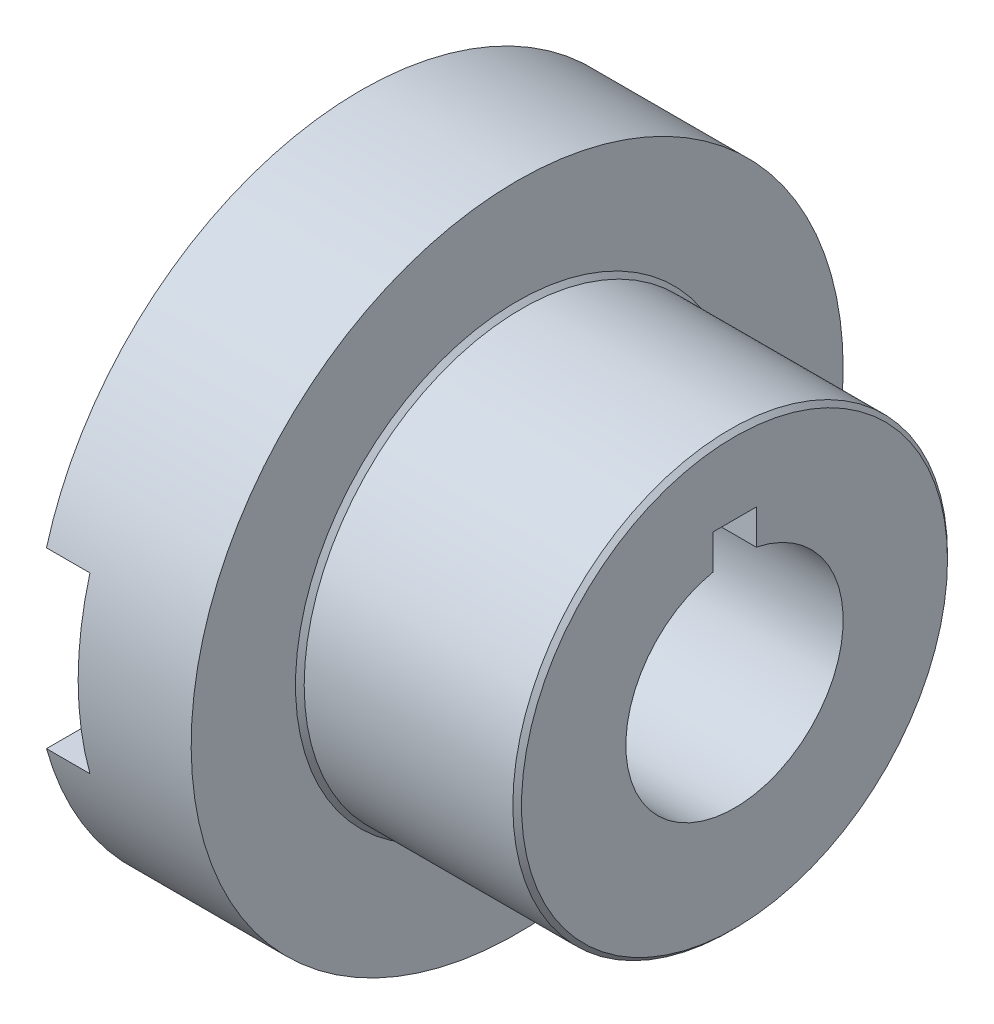
SolidWorks part; units mm, degrees
ref_plane "Front Plane" through (0, 0, 0) normal (0, 0, 1) x (1, 0, 0)
ref_plane "Top Plane" through (0, 0, 0) normal (0, 1, 0) x (1, 0, 0)
ref_plane "Right Plane" through (0, 0, 0) normal (1, 0, 0) x (0, 0, -1)
sketch "Sketch1" plane through (0, 0, 0) normal (1, 0, 0) x (0, 0, -1)
  circle A0 centre (0, 0) radius 75
  dimension "D1" = 150
extrude "Boss-Extrude1" add sketch "Sketch1" along normal blind 36
sketch "Sketch2" plane through (36, 0, 0) normal (1, 0, 0) x (0, 0, -1)
  circle A0 centre (0, 0) radius 50
  dimension "D1" = 100
extrude "Boss-Extrude2" add sketch "Sketch2" along normal blind 50
sketch "Sketch4" plane through (0, 0, 0) normal (-1, 0, 0) x (0, 0, 1)
  line L1 (-72.2842, 20) -> (72.2842, 20)
  line L3 (-72.2842, -20) -> (72.2842, -20)
  circle A0 centre (0, 0) radius 75 construction
  arc A1 (-72.2842, 20) -> (-72.2842, -20) centre (0, 0) ccw
  arc A2 (72.2842, -20) -> (72.2842, 20) centre (0, 0) ccw
  dimension "D1" = 40
  dimension "D2" = 20
extrude "Cut-Extrude2" cut sketch "Sketch4" against normal blind 10
sketch "Sketch5" plane through (86, 0, 0) normal (1, 0, 0) x (0, 0, -1)
  line L0 (0, 0) -> (0, 24.4949) construction
  line L1 (-5, 32.4949) -> (5, 32.4949)
  line L2 (-5, 32.4949) -> (-5, 24.4949)
  line L4 (5, 32.4949) -> (5, 24.4949)
  arc A0 (-5, 24.4949) -> (5, 24.4949) centre (0, 0) ccw
  dimension "D1" = 50
  dimension "D2" = 8
  dimension "D3" = 10
extrude "Cut-Extrude3" cut sketch "Sketch5" against normal up to surface (76 mm away) up to face at (10, 0, 0)
chamfer "Chamfer1" distance 1 angle 45 1 edges at (86, 0, -50)
chamfer "Chamfer2" distance 1 angle 45 1 edges at (36, 0, -50)
